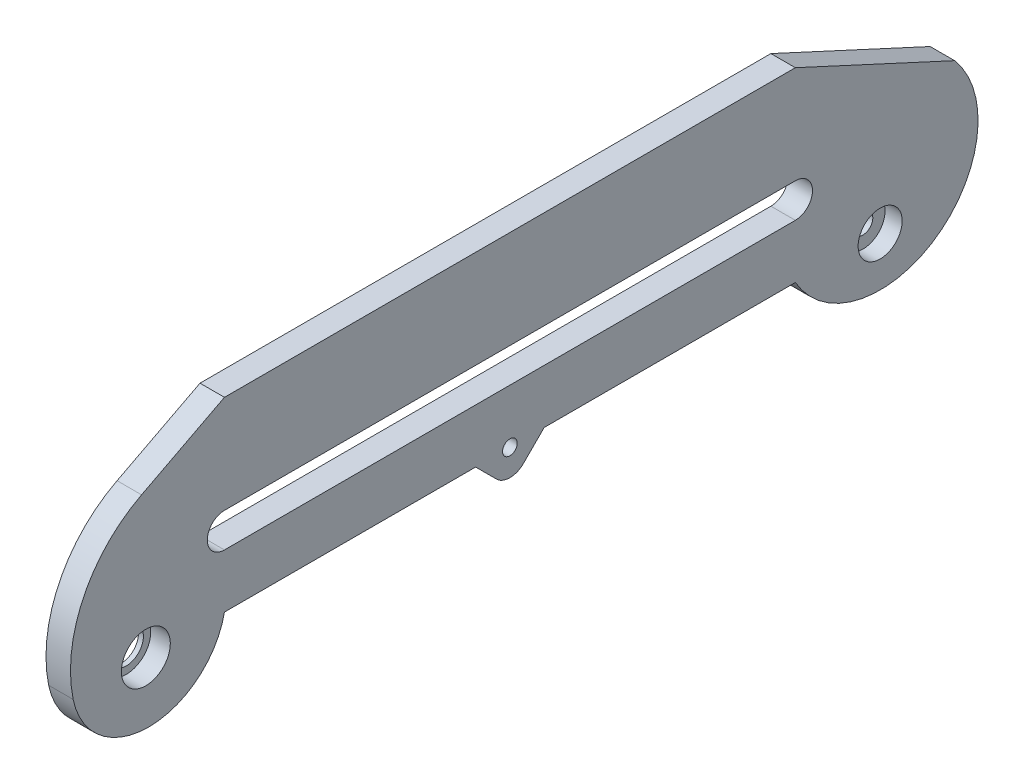
SolidWorks part; units mm, degrees
ref_plane "Front Plane" through (0, 0, 0) normal (0, 0, 1) x (1, 0, 0)
ref_plane "Top Plane" through (0, 0, 0) normal (0, 1, 0) x (1, 0, 0)
ref_plane "Right Plane" through (0, 0, 0) normal (1, 0, 0) x (0, 0, -1)
sketch "Sketch2" plane through (0, 0, 0) normal (1, 0, 0) x (0, 0, -1)
  line L0 (-58.3087, -27) -> (58.3087, -27)
  line L1 (58.3087, -20) -> (-58.3087, -20)
  line L2 (58.3087, 0) -> (-58.3087, 0)
  line L3 (-58.3087, 0) -> (-75.2437, -8.7832)
  line L4 (90.8512, -15.0235) -> (58.3087, 0)
  line L5 (7, -37.9961) -> (58.3087, -37.9961)
  line L6 (-58.3087, -37.9961) -> (-7, -37.9961)
  line L7 (-7, -37.9961) -> (-2.7574, -42.2388)
  line L8 (2.7574, -42.2388) -> (7, -37.9961)
  circle A0 centre (-74.3708, -37.9961) radius 5
  arc A1 (-58.3087, -20) -> (-58.3087, -27) centre (-58.3087, -23.5) ccw
  arc A2 (58.3087, -27) -> (58.3087, -20) centre (58.3087, -23.5) ccw
  circle A3 centre (75.6292, -37.9961) radius 2
  circle A4 centre (0, -38) radius 1.5
  arc A5 (-89.2173, -37.9961) -> (-58.3087, -37.9961) centre (-73.763, -34.823) ccw
  arc A6 (-75.2437, -8.7832) -> (-89.2173, -37.9961) centre (-62.9636, -32.6057) ccw
  arc A7 (58.3087, -37.9961) -> (90.8512, -15.0235) centre (75.6292, -27.9961) ccw
  arc A8 (-2.7574, -42.2388) -> (2.7574, -42.2388) centre (0, -39.4814) ccw
  point P27 (0, 0)
  dimension "D1" = 10
  dimension "D2" = 11
  dimension "D5" = 10.9961
  dimension "D6" = 10.9961
  dimension "D3" = 10.9961
  dimension "D4" = 20
extrude "Boss-Extrude1" add sketch "Sketch2" along normal blind 5
sketch "Sketch3" plane through (5, 0, 0) normal (1, 0, 0) x (0, 0, -1)
  circle A0 centre (75.6292, -37.9961) radius 4.5
  dimension "D1" = 9
extrude "Cut-Extrude1" cut sketch "Sketch3" against normal blind 3.5
sketch "Sketch4" plane through (5, 0, 0) normal (1, 0, 0) x (0, 0, -1)
  circle A0 centre (-74.3708, -37.9961) radius 5
  circle A1 centre (-74.3708, -37.9961) radius 3.5
  dimension "D1" = 7
extrude "Boss-Extrude2" add sketch "Sketch4" along normal blind 1 from surface at -5 starting at face at (0, -29.7715, 5.9943)
